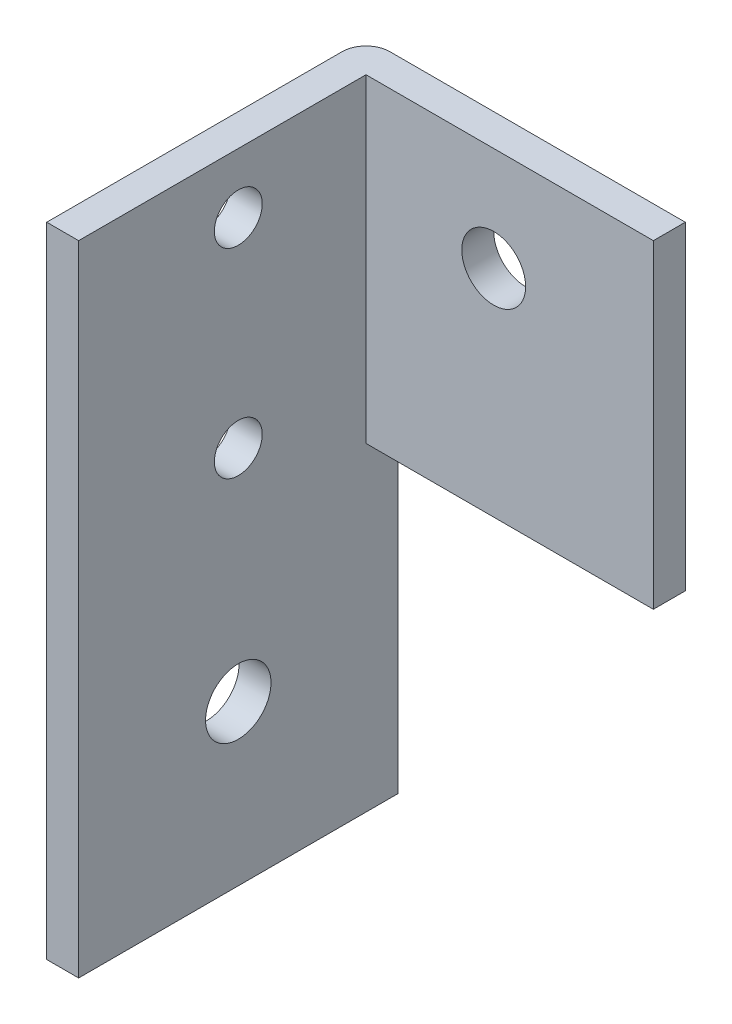
SolidWorks part; units mm, degrees
ref_plane "Front Plane" through (0, 0, 0) normal (0, 0, 1) x (1, 0, 0)
ref_plane "Top Plane" through (0, 0, 0) normal (0, 1, 0) x (1, 0, 0)
ref_plane "Right Plane" through (0, 0, 0) normal (1, 0, 0) x (0, 0, -1)
sketch "Sketch1" plane through (0, 0, 0) normal (0, 1, 0) x (1, 0, 0)
  line L0 (-22.659, -16.8786) -> (-22.659, 20.1214)
  line L1 (-19.659, 23.1214) -> (17.341, 23.1214)
  arc A0 (-22.659, 20.1214) -> (-19.659, 23.1214) centre (-19.659, 20.1214) cw
  point P5 (-22.659, 23.1214)
  dimension "D3" = 3
  dimension "D1" = 40
  dimension "D2" = 40
extrude "Extrude-Thin1" add sketch "Sketch1" along normal blind 80 thin
sketch "Sketch4" plane through (0, 0, -23.1214) normal (0, 0, -1) x (-1, 0, 0)
  line L0 (-17.341, 80) -> (-17.341, 0) construction
  line L1 (19.659, 80) -> (-17.341, 80) construction
  line L2 (19.659, 0) -> (-17.341, 0) construction
  circle A0 centre (2.659, 60) radius 2
  circle A1 centre (2.659, 20) radius 4.1
  dimension "D1" = 4
  dimension "D2" = 8.2
  dimension "D3" = 20
  dimension "D4" = 20
  dimension "D5" = 20
  dimension "D6" = 20
sketch "Sketch5" plane through (-22.659, 0, 0) normal (-1, 0, 0) x (0, 0, 1)
  line L1 (16.8786, 80) -> (16.8786, 0) construction
  line L3 (16.8786, 0) -> (-20.1214, 0) construction
  circle A1 centre (-3.1214, 20) radius 4.1
  circle A2 centre (-3.1214, 47.5) radius 3
  circle A3 centre (-3.1214, 72.5) radius 3
  dimension "D1" = 6
  dimension "D2" = 6
  dimension "D4" = 20
  dimension "D5" = 20
extrude "Cut-Extrude2" cut sketch "Sketch5" against normal blind 10
sketch "Sketch6" plane through (0, 0, -23.1214) normal (0, 0, -1) x (-1, 0, 0)
  line L1 (-38.7536, 40) -> (18.659, 40)
  line L2 (-38.7536, 40) -> (-38.7536, 0)
  line L3 (-38.7536, 0) -> (18.659, 0)
  line L4 (18.659, 40) -> (18.659, 0)
  line L5 (-38.7536, 40) -> (18.659, 0) construction
  line L6 (-38.7536, 0) -> (18.659, 40) construction
  line L7 (19.659, 0) -> (-17.341, 0) construction
  line L8 (18.659, 80) -> (18.659, 0) construction
  point P0 (-10.0473, 20)
  dimension "D1" = 40
  dimension "D2" = 0
  dimension "D3" = 0
extrude "Cut-Extrude3" cut sketch "Sketch6" against normal blind 10
hole_wizard "Ø8.0mm Dowel Hole1" positions "Sketch8" profile "Sketch7" hole size "Ø8.0" standard "ANSI Metric" end condition through all
sketch "Sketch8" plane through (0, 0, -23.1214) normal (0, 0, -1) x (-1, 0, 0)
  line L0 (-17.341, 80) -> (-17.341, 40) construction
  line L1 (19.659, 80) -> (-17.341, 80) construction
  point P0 (2.659, 67)
  dimension "D1" = 20
  dimension "D2" = 13
sketch "Sketch7" plane through (-2.659, 67, -23.1214) normal (1, 0, 0) x (0, 1, 0)
  line L0 (0, 0) -> (0, 40)
  line L1 (0, 40) -> (4, 40)
  line L2 (4, 40) -> (4, 0)
  line L5 (4, 0) -> (0, 0)
  line L11 (0, -6.35) -> (0, 107.95) construction
  dimension "Thru Hole Dia." = 8
  dimension "Thru Hole Depth" = 40
